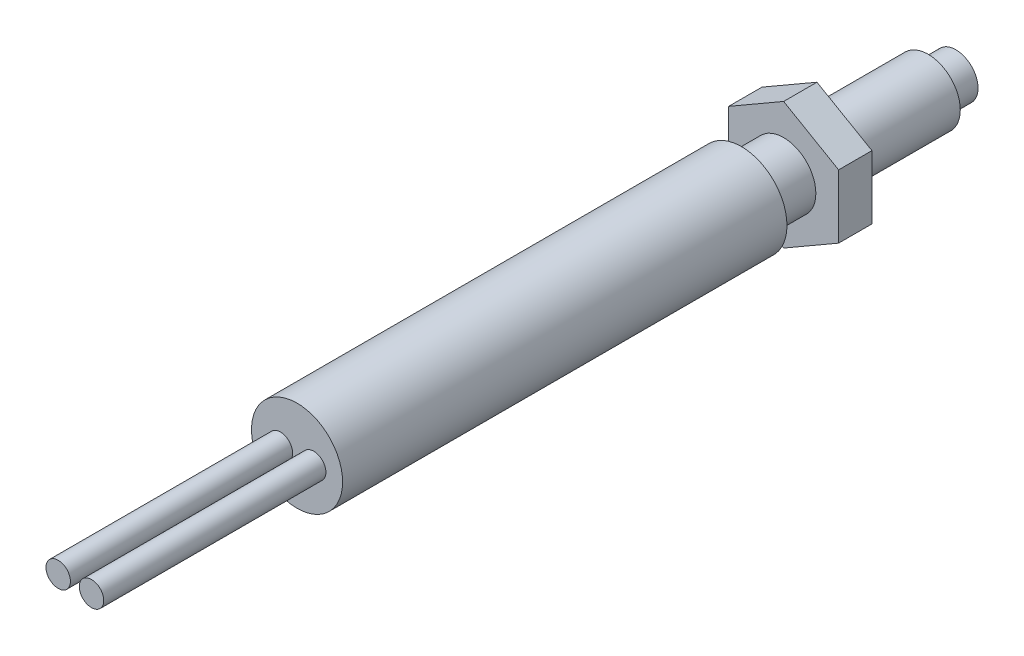
SolidWorks part; units mm, degrees
ref_plane "Plan de face" through (0, 0, 0) normal (0, 0, 1) x (1, 0, 0)
ref_plane "Plan de dessus" through (0, 0, 0) normal (0, 1, 0) x (1, 0, 0)
ref_plane "Plan de droite" through (0, 0, 0) normal (1, 0, 0) x (0, 0, -1)
sketch "Esquisse1" plane through (0, 0, 0) normal (0, 0, 1) x (1, 0, 0)
  circle A0 centre (0, 0) radius 2.9
  dimension "D1" = 5.8
extrude "Boss.-Extru.1" add sketch "Esquisse1" along normal blind 16.8
sketch "Esquisse2" plane through (0, 0, 0) normal (0, 0, -1) x (-1, 0, 0)
  circle A0 centre (0, 0) radius 2
  dimension "D1" = 4
extrude "Boss.-Extru.2" add sketch "Esquisse2" along normal blind 2.5
sketch "Esquisse3" plane through (0, 0, 16.8) normal (0, 0, 1) x (1, 0, 0)
  circle A0 centre (0, 0) radius 4.1
  dimension "D1" = 8.2
extrude "Boss.-Extru.3" add sketch "Esquisse3" along normal blind 40
sketch "Esquisse4" plane through (0, 0, 56.8) normal (0, 0, 1) x (1, 0, 0)
  line L0 (0, 0) -> (0, 1.512) construction
  circle A0 centre (-1.5, 0) radius 1.1
  circle A2 centre (1.5, 0) radius 1.1
  dimension "D1" = 2.2
  dimension "D2" = 3
extrude "Boss.-Extru.4" add sketch "Esquisse4" along normal blind 20
sketch "Esquisse5" plane through (0, 0, 0) normal (0, 0, 1) x (1, 0, 0)
  line L1 (0, -5.7158) -> (4.95, -2.8579)
  line L2 (4.95, -2.8579) -> (4.95, 2.8579)
  line L3 (4.95, 2.8579) -> (0, 5.7158)
  line L4 (0, 5.7158) -> (-4.95, 2.8579)
  line L5 (-4.95, 2.8579) -> (-4.95, -2.8579)
  line L6 (-4.95, -2.8579) -> (0, -5.7158)
  circle A0 centre (0, 0) radius 4.95 construction
  dimension "D1" = 9.9
extrude "Boss.-Extru.5" add sketch "Esquisse5" along normal blind 3 from offset 10
